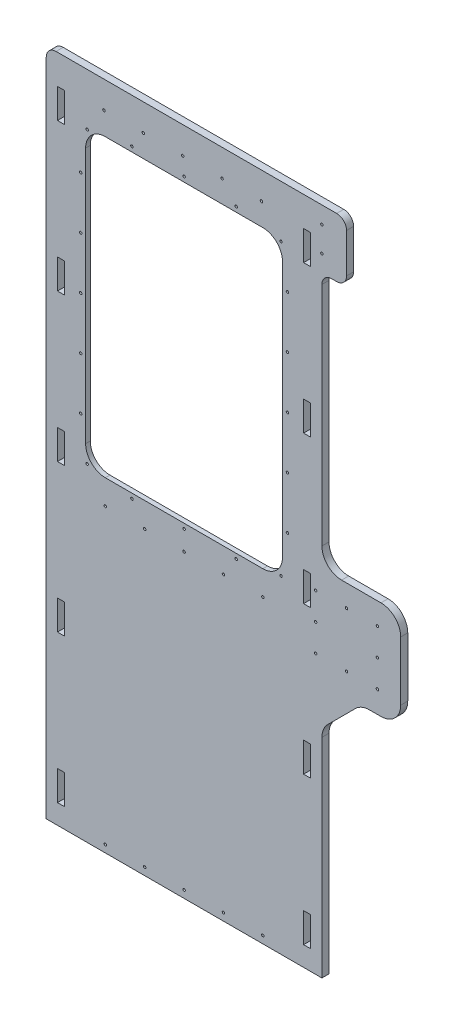
SolidWorks part; units mm, degrees
ref_plane "Front Plane" through (0, 0, 0) normal (0, 0, 1) x (1, 0, 0)
ref_plane "Top Plane" through (0, 0, 0) normal (0, 1, 0) x (1, 0, 0)
ref_plane "Right Plane" through (0, 0, 0) normal (1, 0, 0) x (0, 0, -1)
sketch "Model" plane through (0, 0, 0) normal (0, 0, 1) x (1, 0, 0)
  line L24 (797.921, 645.521) -> (726.079, 573.679)
  line L25 (0, 0) -> (711.2, 0)
  line L26 (0, 0) -> (0, 1701.9397)
  line L27 (25.4, 1727.3397) -> (711.2, 1727.3397)
  line L28 (711.2, 0) -> (711.2, 537.758)
  line L29 (558.8, 838.3397) -> (152.4, 838.3397)
  line L30 (609.6, 889.1397) -> (609.6, 1549.5397)
  line L31 (558.8, 1600.3397) -> (152.4, 1600.3397)
  line L32 (101.6, 889.1397) -> (101.6, 1549.5397)
  line L33 (609.6, 838.3397) -> (101.6, 1600.3397) construction
  line L34 (609.6, 1600.3397) -> (101.6, 838.3397) construction
  line L35 (762, 914.4) -> (863.6, 914.4)
  line L37 (833.842, 660.4) -> (863.6, 660.4)
  line L38 (914.4, 863.6) -> (914.4, 711.2)
  line L39 (711.2, 965.2) -> (711.2, 1549.5397)
  line L41 (711.2, 1727.3397) -> (749.3, 1727.3397)
  line L43 (736.6, 1574.9397) -> (749.3, 1574.9397)
  line L44 (774.7, 1701.9397) -> (774.7, 1600.3397)
  arc A16 (762, 914.4) -> (711.2, 965.2) centre (762, 965.2) cw
  arc A17 (152.4, 838.3397) -> (101.6, 889.1397) centre (152.4, 889.1397) cw
  arc A18 (558.8, 838.3397) -> (609.6, 889.1397) centre (558.8, 889.1397) ccw
  arc A19 (609.6, 1549.5397) -> (558.8, 1600.3397) centre (558.8, 1549.5397) ccw
  arc A20 (152.4, 1600.3397) -> (101.6, 1549.5397) centre (152.4, 1549.5397) ccw
  arc A21 (726.079, 573.679) -> (711.2, 537.758) centre (762, 537.758) ccw
  arc A22 (797.921, 645.521) -> (833.842, 660.4) centre (833.842, 609.6) cw
  arc A23 (863.6, 660.4) -> (914.4, 711.2) centre (863.6, 711.2) ccw
  arc A24 (863.6, 914.4) -> (914.4, 863.6) centre (863.6, 863.6) cw
  arc A25 (749.3, 1727.3397) -> (774.7, 1701.9397) centre (749.3, 1701.9397) cw
  arc A26 (749.3, 1574.9397) -> (774.7, 1600.3397) centre (749.3, 1600.3397) ccw
  arc A27 (711.2, 1549.5397) -> (736.6, 1574.9397) centre (736.6, 1549.5397) cw
  arc A28 (0, 1701.9397) -> (25.4, 1727.3397) centre (25.4, 1701.9397) cw
  point P54 (355.6, 1219.3397)
  point P67 (711.2, 914.4)
  point P89 (914.4, 660.4)
  point P92 (914.4, 914.4)
  point P95 (774.7, 1727.3397)
  point P99 (774.7, 1574.9397)
  point P104 (0, 1727.3397)
  dimension "D31" = 50.8
  dimension "D36" = 50.8
  dimension "D39" = 50.8
  dimension "D40" = 50.8
  dimension "D41" = 25.4
  dimension "D42" = 25.4
  dimension "D1" = 0
  dimension "D5" = 0
  dimension "D6" = 711.2
  dimension "D7" = 584.3397
  dimension "D8" = 101.6
  dimension "D26" = 711.2
  dimension "D27" = 914.4
  dimension "D28" = 203.2
  dimension "D29" = 254
  dimension "D30" = 45
  dimension "D32" = 152.4
  dimension "D33" = 63.5
  dimension "D34" = 508
  dimension "D35" = 762
  dimension "D37" = 127
  dimension "D38" = 355.6
other "AlignGroup1"
other "AlignGroup2"
other "AlignGroup3"
other "AlignGroup4"
other "AlignGroup5"
other "AlignGroup6"
extrude "Boss-Extrude1" add sketch "Model" along normal blind 18.288
sketch "Sketch1" plane through (0, 0, 18.288) normal (0, 0, 1) x (1, 0, 0)
  line L1 (663.956, 127) -> (682.244, 127)
  line L2 (663.956, 127) -> (663.956, 50.8)
  line L3 (663.956, 50.8) -> (682.244, 50.8)
  line L4 (682.244, 127) -> (682.244, 50.8)
  line L6 (0, 0) -> (711.2, 0) construction
  line L7 (711.2, 0) -> (711.2, 537.758) construction
  line L8 (0, 1701.9397) -> (0, 0) construction
  line L9 (47.244, 127) -> (28.956, 127)
  line L10 (47.244, 127) -> (47.244, 50.8)
  line L11 (47.244, 50.8) -> (28.956, 50.8)
  line L12 (28.956, 127) -> (28.956, 50.8)
  point P6 (673.1, 50.8)
  point P13 (38.1, 50.8)
  dimension "D1" = 18.288
  dimension "D2" = 38.1
  dimension "D3" = 50.8
  dimension "D4" = 76.2
  dimension "D5" = 38.1
extrude "Mortise cuts" cut sketch "Sketch1" against normal through all
pattern_linear "LPattern1" count 5 spacing 381 along (0, 1, 0) of "Mortise cuts"
sketch "Sketch2" plane through (0, 0, 18.288) normal (0, 0, 1) x (1, 0, 0)
  line L24 (635, 889.1397) -> (635, 1549.5397)
  line L25 (152.4, 812.9397) -> (558.8, 812.9397)
  line L26 (76.2, 1549.5397) -> (76.2, 889.1397)
  line L27 (558.8, 1625.7397) -> (152.4, 1625.7397)
  line L28 (635, 889.1397) -> (635, 1549.5397)
  line L29 (152.4, 812.9397) -> (558.8, 812.9397)
  line L30 (76.2, 1549.5397) -> (76.2, 889.1397)
  line L31 (558.8, 1625.7397) -> (152.4, 1625.7397)
  arc A20 (635, 1549.5397) -> (558.8, 1625.7397) centre (558.8, 1549.5397) ccw
  arc A21 (558.8, 812.9397) -> (635, 889.1397) centre (558.8, 889.1397) ccw
  arc A22 (76.2, 889.1397) -> (152.4, 812.9397) centre (152.4, 889.1397) ccw
  arc A23 (152.4, 1625.7397) -> (76.2, 1549.5397) centre (152.4, 1549.5397) ccw
  arc A24 (635, 1549.5397) -> (558.8, 1625.7397) centre (558.8, 1549.5397) ccw
  arc A25 (558.8, 812.9397) -> (635, 889.1397) centre (558.8, 889.1397) ccw
  arc A26 (76.2, 889.1397) -> (152.4, 812.9397) centre (152.4, 889.1397) ccw
  arc A27 (152.4, 1625.7397) -> (76.2, 1549.5397) centre (152.4, 1549.5397) ccw
  dimension "D1" = 25.4
extrude "Window Recess" cut sketch "Sketch2" against normal blind 6.35
sketch "Sketch3" plane through (0, 0, 11.938) normal (0, 0, 1) x (1, 0, 0)
  line L0 (355.6, 1625.7397) -> (355.6, 812.9397) construction
  line L1 (558.8, 1625.7397) -> (152.4, 1625.7397) construction
  line L2 (152.4, 812.9397) -> (558.8, 812.9397) construction
  line L3 (76.2, 1219.3397) -> (635, 1219.3397) construction
  line L4 (76.2, 1549.5397) -> (76.2, 889.1397) construction
  line L5 (635, 889.1397) -> (635, 1549.5397) construction
  line L6 (98.5185, 1603.4213) -> (612.6815, 835.2582) construction
  line L7 (612.6815, 1603.4213) -> (98.5185, 835.2582) construction
  arc A0 (152.4, 1625.7397) -> (76.2, 1549.5397) centre (152.4, 1549.5397) ccw construction
  arc A1 (558.8, 812.9397) -> (635, 889.1397) centre (558.8, 889.1397) ccw construction
  arc A2 (635, 1549.5397) -> (558.8, 1625.7397) centre (558.8, 1549.5397) ccw construction
  arc A3 (76.2, 889.1397) -> (152.4, 812.9397) centre (152.4, 889.1397) ccw construction
  circle A4 centre (105.5827, 1592.8673) radius 3.175
  circle A5 centre (605.6173, 1592.8673) radius 3.175
  circle A7 centre (605.6173, 845.8122) radius 3.175
  circle A8 centre (105.5827, 845.8122) radius 3.175
  dimension "D1" = 12.7
  dimension "D4" = 12.7
  dimension "D5" = 6.35
  dimension "D6" = 12.7
  dimension "D7" = 12.7
extrude "Cut-Extrude4" cut sketch "Sketch3" against normal through all
sketch "Sketch6" plane through (0, 0, 11.938) normal (0, 0, 1) x (1, 0, 0)
  line L0 (76.2, 1219.3397) -> (635, 1219.3397) construction
  line L1 (76.2, 1549.5397) -> (76.2, 889.1397) construction
  circle A0 centre (88.9, 1219.3397) radius 3.175
  dimension "D1" = 12.7
extrude "Cut-Extrude5" cut sketch "Sketch6" against normal through all
pattern_linear "LPattern2" count 3 spacing 134.62 along (0, -1, 0) count 3 spacing 134.62 along (0, 1, 0) of "Cut-Extrude5"
ref_plane "Plane1" through (355.6, 0, 0) normal (-1, 0, 0) x (0, 0, 1)
mirror "Mirror1" about plane through (355.6, 0, 0) normal (-1, 0, 0) of "LPattern2", "Cut-Extrude5"
sketch "Sketch7" plane through (0, 0, 11.938) normal (0, 0, 1) x (1, 0, 0)
  line L0 (355.6, 1625.7397) -> (355.6, 812.9397) construction
  line L1 (558.8, 1625.7397) -> (152.4, 1625.7397) construction
  circle A0 centre (355.6, 1613.0397) radius 3.175
  dimension "D1" = 12.7
extrude "Cut-Extrude6" cut sketch "Sketch7" against normal through all
pattern_linear "LPattern3" count 2 spacing 134.62 along (1, 0, 0) count 2 spacing 134.62 along (-1, 0, 0) of "Cut-Extrude6"
ref_plane "Plane2" through (0, 1219.3397, 0) normal (0, -1, 0) x (-1, 0, 0)
mirror "Mirror2" about plane through (0, 1219.3397, 0) normal (0, -1, 0) of "LPattern3", "Cut-Extrude6"
sketch "Sketch10" plane through (0, 1727.3397, 0) normal (0, 1, 0) x (1, 0, 0)
  line L0 (749.3, -9.144) -> (25.4, -9.144)
  line L1 (749.3, -18.288) -> (749.3, 0) construction
  line L2 (25.4, -18.288) -> (25.4, 0) construction
ref_plane "Plane3" through (0, 0, 9.144) normal (0, 0, -1) x (-1, 0, 0)
mirror "Mirror4" about plane through (0, 0, 9.144) normal (0, 0, -1) of "Boss-Extrude1", "LPattern1", "Window Recess", "Cut-Extrude4", "Cut-Extrude5", "LPattern2", "Mirror1", "Cut-Extrude6", "LPattern3", "Mirror2", "Mortise cuts"
sketch "Sketch11" plane through (0, 0, 0) normal (0, 0, -1) x (-1, 0, 0)
  line L0 (0, 0) -> (-711.2, 0) construction
  line L1 (-609.6, 793.75) -> (-101.6, 793.75) construction
  line L2 (-609.6, 793.75) -> (-609.6, 755.65) construction
  line L3 (-609.6, 755.65) -> (-101.6, 755.65) construction
  line L4 (-101.6, 793.75) -> (-101.6, 755.65) construction
  line L5 (-355.6, 755.65) -> (-355.6, 793.75) construction
  line L6 (-609.6, 774.7) -> (-101.6, 774.7) construction
  line L8 (0, 1701.9397) -> (0, 0) construction
  line L9 (-609.6, 38.1) -> (-101.6, 38.1) construction
  line L10 (-609.6, 38.1) -> (-609.6, 0) construction
  line L11 (-609.6, 0) -> (-101.6, 0) construction
  line L12 (-101.6, 38.1) -> (-101.6, 0) construction
  circle A0 centre (-152.4, 774.7) radius 3.175
  circle A1 centre (-254, 774.7) radius 3.175
  circle A2 centre (-355.6, 774.7) radius 3.175
  circle A3 centre (-457.2, 774.7) radius 3.175
  circle A4 centre (-558.8, 774.7) radius 3.175
  circle A5 centre (-152.4, 19.05) radius 3.175
  circle A6 centre (-254, 19.05) radius 3.175
  circle A7 centre (-355.6, 19.05) radius 3.175
  circle A8 centre (-457.2, 19.05) radius 3.175
  circle A9 centre (-558.8, 19.05) radius 3.175
  point P164 (-355.6, 774.7)
  dimension "D5" = 6.35
  dimension "D6" = 50.8
  dimension "D1" = 508
  dimension "D2" = 38.1
  dimension "D3" = 774.7
  dimension "D4" = 355.6
  dimension "D7" = 5
  dimension "D8" = 2
extrude "Cut-Extrude7" cut sketch "Sketch11" against normal through all
sketch "Sketch12" plane through (0, 0, 18.288) normal (0, 0, 1) x (1, 0, 0)
  circle A0 centre (854.456, 858.012) radius 3.175
  circle A1 centre (774.7, 858.012) radius 3.175
  circle A2 centre (694.944, 858.012) radius 3.175
  circle A3 centre (694.944, 787.4) radius 3.175
  circle A4 centre (694.944, 716.788) radius 3.175
  circle A5 centre (774.7, 716.788) radius 3.175
  circle A6 centre (854.456, 716.788) radius 3.175
  circle A7 centre (854.456, 787.4) radius 3.175
extrude "Cut-Extrude8" cut sketch "Sketch12" against normal through all
sketch "Sketch13" plane through (0, 0, 18.288) normal (0, 0, 1) x (1, 0, 0)
  circle A0 centre (148.844, 1657.4897) radius 3.175
  circle A1 centre (250.444, 1657.4897) radius 3.175
  circle A2 centre (352.044, 1657.4897) radius 3.175
  circle A3 centre (453.644, 1657.4897) radius 3.175
  circle A4 centre (555.244, 1657.4897) radius 3.175
  dimension "D1" = 5
extrude "Cut-Extrude9" cut sketch "Sketch13" against normal through all
sketch "Sketch14" plane through (0, 0, 18.288) normal (0, 0, 1) x (1, 0, 0)
  circle A0 centre (711.2, 1683.549) radius 3.175
  circle A1 centre (711.2, 1618.525) radius 3.175
extrude "Cut-Extrude10" cut sketch "Sketch14" against normal through all
